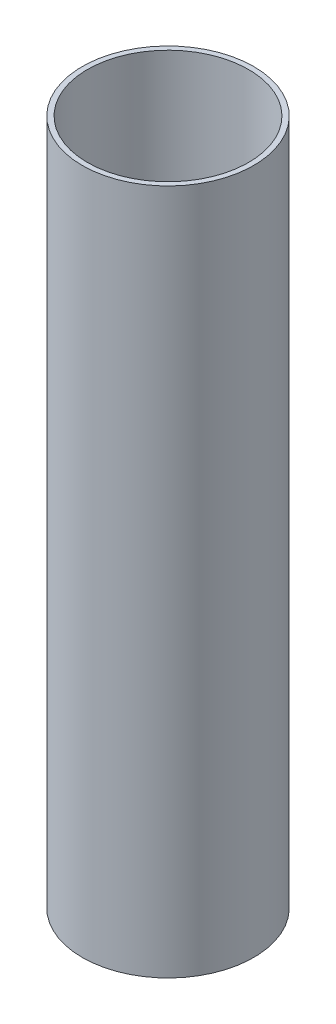
SolidWorks part; units mm, degrees
ref_plane "前视基准面" through (0, 0, 0) normal (0, 0, 1) x (1, 0, 0)
ref_plane "上视基准面" through (0, 0, 0) normal (0, 1, 0) x (1, 0, 0)
ref_plane "右视基准面" through (0, 0, 0) normal (1, 0, 0) x (0, 0, -1)
sketch "草图1" plane through (0, 0, 0) normal (0, 1, 0) x (1, 0, 0)
  circle A0 centre (0, 0) radius 25
  circle A1 centre (0, 0) radius 23.5
  dimension "D1" = 50
  dimension "D2" = 47
extrude "凸台-拉伸1" add sketch "草图1" along normal blind 200
